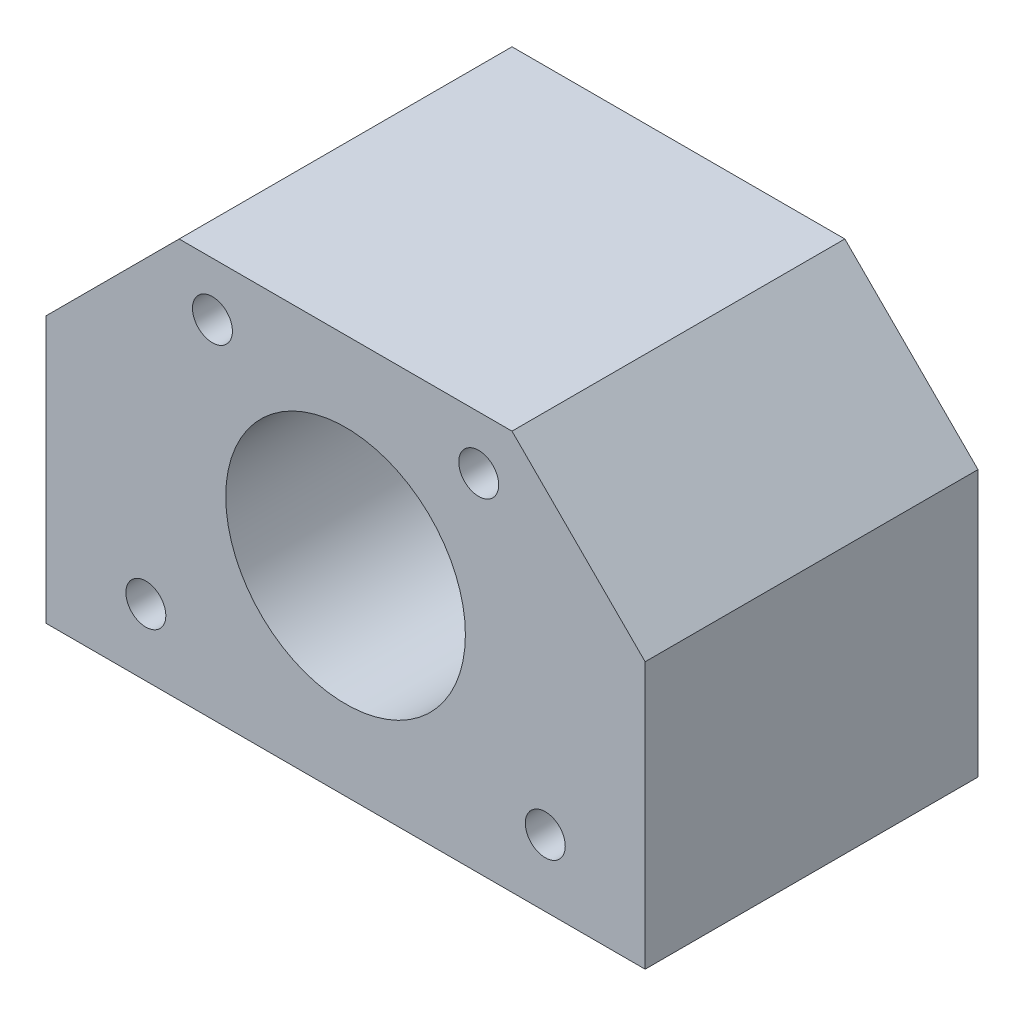
SolidWorks part; units mm, degrees
material "1023 Chapa de acero al carbono (SS)"
ref_plane "Front" through (0, 0, 0) normal (0, 0, 1) x (1, 0, 0)
ref_plane "Top" through (0, 0, 0) normal (0, 1, 0) x (1, 0, 0)
ref_plane "Right" through (0, 0, 0) normal (1, 0, 0) x (0, 0, -1)
sketch "Croquis1" plane through (0, 0, 0) normal (0, 0, 1) x (1, 0, 0)
  line L0 (-22.5, 5) -> (-12.5, 15)
  line L1 (-22.5, -15) -> (22.5, -15)
  line L2 (-22.5, -15) -> (-22.5, 5)
  line L3 (-12.5, 15) -> (12.5, 15)
  line L4 (22.5, -15) -> (22.5, 5)
  line L5 (-22.5, -15) -> (22.5, 15) construction
  line L6 (-22.5, 15) -> (22.5, -15) construction
  line L7 (12.5, 15) -> (22.5, 5)
  circle A0 centre (0, 0) radius 9
  dimension "D1" = 18
  dimension "D2" = 45
  dimension "D3" = 30
extrude "Saliente-Extruir1" add sketch "Croquis1" along normal blind 25
sketch "Croquis2" plane through (0, 0, 25) normal (0, 0, 1) x (1, 0, 0)
  line L1 (-22.5, -15) -> (22.5, -15) construction
  line L2 (0, 0) -> (0, 5.9848) construction
  line L3 (12.5, 15) -> (-12.5, 15) construction
  circle A0 centre (-15, -10) radius 1.5
  circle A1 centre (15, -10) radius 1.5
  circle A2 centre (-10, 11) radius 1.5
  circle A3 centre (10, 11) radius 1.5
  dimension "D1" = 30
  dimension "D2" = 3
  dimension "D3" = 4
  dimension "D4" = 20
  dimension "5" = 5
extrude "Cortar-Extruir1" cut sketch "Croquis2" against normal blind 25
